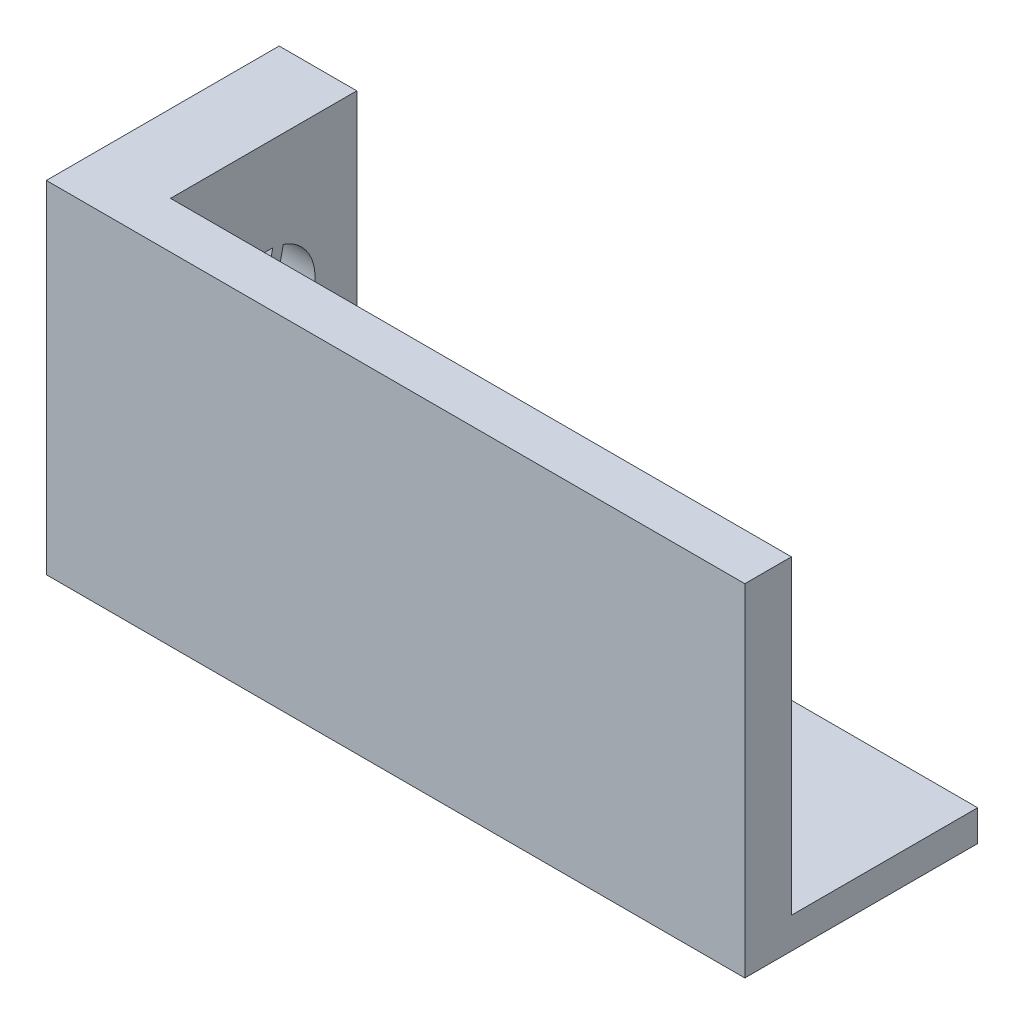
SolidWorks part; units mm, degrees
ref_plane "Plan de face" through (0, 0, 0) normal (0, 0, 1) x (1, 0, 0)
ref_plane "Plan de dessus" through (0, 0, 0) normal (0, 1, 0) x (1, 0, 0)
ref_plane "Plan de droite" through (0, 0, 0) normal (1, 0, 0) x (0, 0, -1)
sketch "Esquisse1" plane through (0, 0, 0) normal (0, 0, 1) x (1, 0, 0)
  line L1 (-21.1511, 14.9242) -> (23.8489, 14.9242)
  line L2 (-21.1511, 14.9242) -> (-21.1511, -5.0758)
  line L3 (-21.1511, -5.0758) -> (23.8489, -5.0758)
  line L4 (23.8489, 14.9242) -> (23.8489, -5.0758)
  dimension "D1" = 45
  dimension "D2" = 20
extrude "Boss.-Extru.1" add sketch "Esquisse1" along normal blind 3
sketch "Esquisse2" plane through (-21.1511, 0, 0) normal (-1, 0, 0) x (0, 0, 1)
  line L0 (3, -5.0758) -> (0, -5.0758) construction
  line L1 (3, 14.9242) -> (-12, 14.9242)
  line L2 (3, 14.9242) -> (3, -5.0758)
  line L3 (3, -5.0758) -> (-12, -5.0758)
  line L4 (-12, 14.9242) -> (-12, -5.0758)
  dimension "D1" = 15
extrude "Boss.-Extru.2" add sketch "Esquisse2" against normal blind 5
sketch "Esquisse3" plane through (0, -5.0758, 0) normal (0, -1, 0) x (1, 0, 0)
  line L0 (23.8489, 3) -> (23.8489, 0) construction
  line L1 (-21.1511, 3) -> (23.8489, 3)
  line L2 (-21.1511, 3) -> (-21.1511, -12)
  line L3 (-21.1511, -12) -> (23.8489, -12)
  line L4 (23.8489, 3) -> (23.8489, -12)
  line L5 (-16.1511, -12) -> (-21.1511, -12) construction
extrude "Boss.-Extru.3" add sketch "Esquisse3" along normal blind 2
sketch "Esquisse4" plane through (-16.1511, 0, 0) normal (1, 0, 0) x (0, 0, -1)
  circle A0 centre (6.3116, 5.8778) radius 3
  dimension "D1" = 6
extrude "Enlèv. mat.-Extru.1" cut sketch "Esquisse4" against normal up to surface (5 mm away) contours A0
sketch "Esquisse5" plane through (-16.1511, 0, 0) normal (1, 0, 0) x (0, 0, -1)
  line L0 (6.6172, 9.0418) -> (5.1916, 2.3996)
  line L1 (5.1916, 2.3996) -> (5.8779, 2.2523)
  line L2 (5.8779, 2.2523) -> (7.335, 9.0418)
  line L3 (7.335, 9.0418) -> (6.6172, 9.0418)
  line L4 (5.3731, 3.888) -> (6.2723, 8.0774) construction
  line L5 (7.25, 7.8676) -> (6.3508, 3.6781) construction
extrude "Boss.-Extru.4" add sketch "Esquisse5" against normal up to surface (5 mm away)
